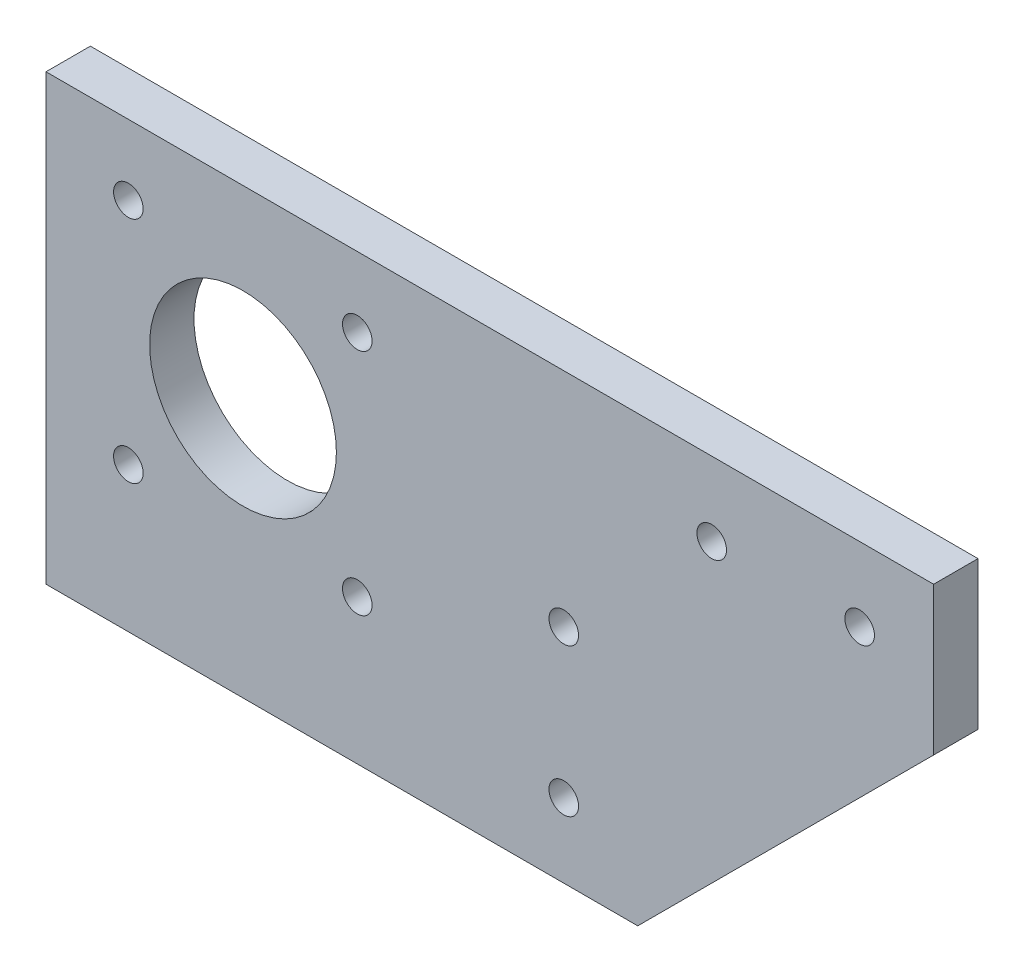
SolidWorks part; units mm, degrees
ref_plane "Front Plane" through (0, 0, 0) normal (0, 0, 1) x (1, 0, 0)
ref_plane "Top Plane" through (0, 0, 0) normal (0, 1, 0) x (1, 0, 0)
ref_plane "Right Plane" through (0, 0, 0) normal (1, 0, 0) x (0, 0, -1)
sketch "Sketch1" plane through (0, 0, 0) normal (0, 0, 1) x (1, 0, 0)
  line L0 (20, -60) -> (60, -20)
  line L1 (0, 0) -> (60, 0)
  line L2 (0, 0) -> (0, -60) construction
  line L3 (0, -60) -> (20, -60)
  line L4 (60, 0) -> (60, -20)
  line L5 (10, -60) -> (10, -50) construction
  line L6 (10, -50) -> (10, -30) construction
  line L7 (10, -30) -> (10, -10) construction
  line L8 (10, -10) -> (30, -10) construction
  line L9 (30, -10) -> (50, -10) construction
  line L10 (50, -10) -> (60, -10) construction
  line L12 (-60, -60) -> (0, -60)
  line L13 (-60, -60) -> (-60, 0)
  line L14 (-60, 0) -> (0, 0)
  line L15 (0, -60) -> (0, 0) construction
  circle A0 centre (50, -10) radius 2
  circle A1 centre (30, -10) radius 2
  circle A2 centre (10, -50) radius 2
  circle A3 centre (10, -30) radius 2
  circle A4 centre (-33.3656, -24.93) radius 12.626
  dimension "D3" = 4
  dimension "D1" = 60
  dimension "D2" = 20
  dimension "D4" = 10
  dimension "D5" = 30
  dimension "D6" = 30
  dimension "D7" = 10
  dimension "D8" = 60
  dimension "D9" = 60
extrude "Boss-Extrude1" add sketch "Sketch1" along normal blind 6
sketch "Sketch2" plane through (0, 0, 0) normal (0, 0, -1) x (-1, 0, 0)
  line L0 (9.9156, 0) -> (9.9156, -6.7) construction
  line L1 (-60, 0) -> (60, 0) construction
  line L2 (9.9156, 0) -> (17.9156, 0) construction
  line L3 (17.9156, 0) -> (17.9156, -9.48) construction
  line L4 (17.9156, -11.48) -> (17.9156, -40.43) construction
  line L5 (17.9156, -9.48) -> (48.8656, -9.48) construction
  line L6 (17.9156, -25.955) -> (33.3906, -25.955) construction
  line L7 (33.3906, -9.48) -> (33.3906, -25.955) construction
  circle A0 centre (17.9156, -9.48) radius 2
  circle A1 centre (17.9156, -40.43) radius 2
  circle A2 centre (48.8656, -9.48) radius 2
  circle A3 centre (48.8656, -40.43) radius 2
  point P14 (19.9156, -9.48)
  point P16 (17.9156, -38.43)
  dimension "D3" = 4
  dimension "D4" = 4
  dimension "D1" = 8
  dimension "D2" = 9.48
  dimension "D5" = 26.95
  dimension "D6" = 28.95
extrude "Cut-Extrude1" cut sketch "Sketch2" against normal blind 10
